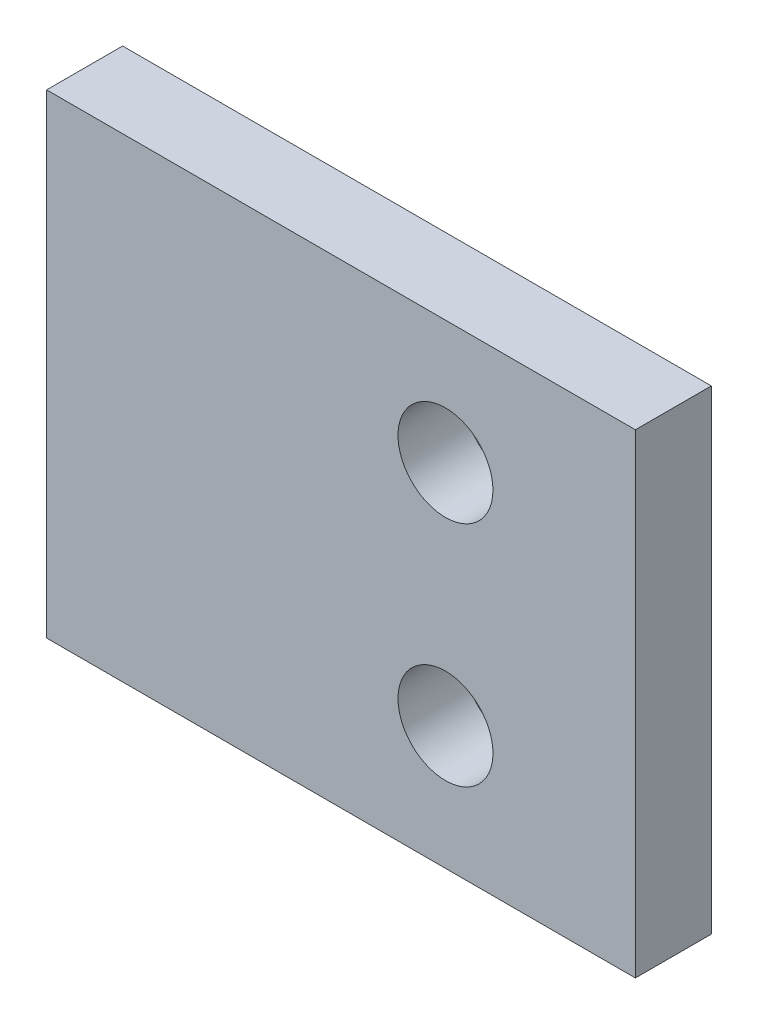
SolidWorks part; units mm, degrees
ref_plane "Front Plane" through (0, 0, 0) normal (0, 0, 1) x (1, 0, 0)
ref_plane "Top Plane" through (0, 0, 0) normal (0, 1, 0) x (1, 0, 0)
ref_plane "Right Plane" through (0, 0, 0) normal (1, 0, 0) x (0, 0, -1)
sketch "Sketch1" plane through (0, 0, 0) normal (0, 0, 1) x (1, 0, 0)
  line L1 (-20, -12.5) -> (20, -12.5)
  line L2 (-20, -12.5) -> (-20, 12.5)
  line L3 (-20, 12.5) -> (20, 12.5)
  line L4 (20, -12.5) -> (20, 12.5)
  line L5 (-20, -12.5) -> (20, 12.5) construction
  line L6 (-20, 12.5) -> (20, -12.5) construction
  point P0 (0, 0)
extrude "Boss-Extrude1" add sketch "Sketch1" along normal blind 4
sketch "Sketch7" plane through (0, 0, 0) normal (0, 0, 1) x (1, 0, 0)
  line L0 (-20, -12.5) -> (20, -12.5) construction
  line L1 (-20, 12.5) -> (-11, 12.5)
  line L2 (-20, 12.5) -> (-20, -12.5)
  line L3 (-20, -12.5) -> (-11, -12.5)
  line L4 (-11, 12.5) -> (-11, -12.5)
extrude "Cut-Extrude5" cut sketch "Sketch7" along normal blind 21
sketch "Sketch8" plane through (0, 0, 0) normal (0, 0, 1) x (1, 0, 0)
  line L1 (20, 12.5) -> (40, 12.5)
  line L2 (20, 12.5) -> (20, -12.5)
  line L3 (20, -12.5) -> (40, -12.5)
  line L4 (40, 12.5) -> (40, -12.5)
extrude "Boss-Extrude2" add sketch "Sketch8" along normal blind 4
sketch "Sketch9" plane through (0, 0, 0) normal (0, 0, 1) x (1, 0, 0)
  line L0 (30, 6) -> (30, 12.5) construction
  line L1 (40, 12.5) -> (-11, 12.5) construction
  line L2 (30, -6) -> (30, -12.5) construction
  line L3 (-11, -12.5) -> (40, -12.5) construction
  circle A0 centre (30, 6) radius 2.5
  circle A1 centre (30, -6) radius 2.5
extrude "Cut-Extrude6" cut sketch "Sketch9" along normal through all both and the other way through all
sketch "Sketch10" plane through (0, 0, 0) normal (0, 0, 1) x (1, 0, 0)
  line L0 (32.7052, 0.6444) -> (32.7052, -0.6444)
  line L2 (27.3249, -0.6294) -> (27.3249, 0.6294)
  arc A1 (27.3249, -0.6294) -> (32.7052, -0.6444) centre (30, -6) ccw
  arc A2 (32.7052, 0.6444) -> (27.3249, 0.6294) centre (30, 6) ccw
extrude "Cut-Extrude7" cut sketch "Sketch10" along normal blind 0.5
fillet "Fillet1" radius 1 4 edges at (27.3249, -0.6294, 0.25) (27.3249, 0.6294, 0.25) (32.7052, -0.6444, 0.25) (32.7052, 0.6444, 0.25)
sketch "Sketch11" plane through (0, 0, 0) normal (0, 0, 1) x (1, 0, 0)
  line L0 (-11, -12.5) -> (40, -12.5) construction
  line L1 (-11, 12.5) -> (9, 12.5)
  line L2 (-11, 12.5) -> (-11, -12.5)
  line L3 (-11, -12.5) -> (9, -12.5)
  line L4 (9, 12.5) -> (9, -12.5)
extrude "Cut-Extrude8" cut sketch "Sketch11" along normal blind 10
